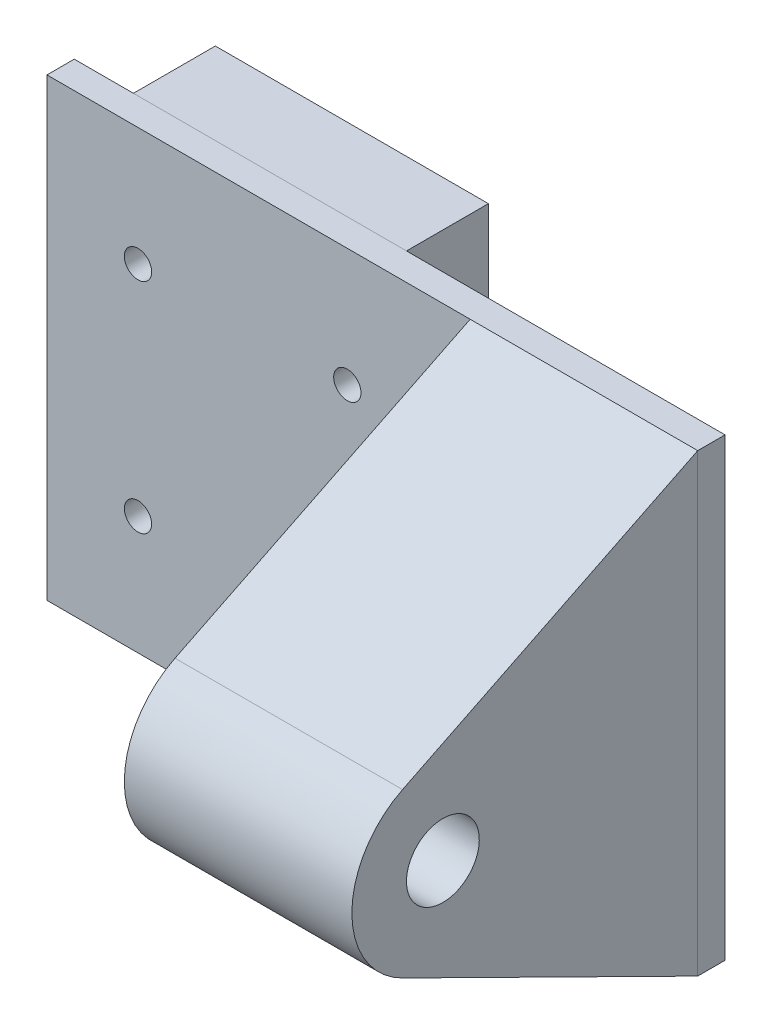
SolidWorks part; units mm, degrees
ref_plane "Plan de face" through (0, 0, 0) normal (0, 0, 1) x (1, 0, 0)
ref_plane "Plan de dessus" through (0, 0, 0) normal (0, 1, 0) x (1, 0, 0)
ref_plane "Plan de droite" through (0, 0, 0) normal (1, 0, 0) x (0, 0, -1)
sketch "Esquisse1" plane through (0, 0, 0) normal (0, 0, 1) x (1, 0, 0)
  line L1 (0, 0) -> (30, 0)
  line L2 (0, 0) -> (0, 50)
  line L3 (0, 50) -> (30, 50)
  line L4 (30, 0) -> (30, 50)
  dimension "D1" = 30
  dimension "D2" = 50
extrude "Boss.-Extru.1" add sketch "Esquisse1" along normal blind 9
sketch "Esquisse2" plane through (0, 0, 9) normal (0, 0, 1) x (1, 0, 0)
  line L0 (0, 0) -> (30, 0) construction
  line L1 (-6.5, 50) -> (65, 50)
  line L2 (-6.5, 50) -> (-6.5, 0)
  line L3 (-6.5, 0) -> (65, 0)
  line L4 (65, 50) -> (65, 0)
  line L5 (30, 50) -> (0, 50) construction
  line L6 (30, 50) -> (0, 50) construction
  line L7 (0, 50) -> (0, 0) construction
  point P7 (15, 50)
  dimension "D1" = 50
  dimension "D2" = 6.5
extrude "Boss.-Extru.2" add sketch "Esquisse2" along normal blind 3 separate body
sketch "Esquisse3" plane through (65, 0, 0) normal (1, 0, 0) x (0, 0, -1)
  line L0 (-12, 50) -> (-12, 0)
  line L1 (-12, 0) -> (-44.4322, 16.0359)
  line L3 (-44.4322, 33.9641) -> (-12, 50)
  line L4 (0, 0) -> (0, 50) construction
  circle A0 centre (-40, 25) radius 4
  arc A1 (-44.4322, 33.9641) -> (-44.4322, 16.0359) centre (-40, 25) ccw
  dimension "D1" = 8
  dimension "D2" = 20
  dimension "D3" = 40
  dimension "D4" = 25
extrude "Boss.-Extru.3" add sketch "Esquisse3" against normal blind 25 separate body
sketch "Esquisse4" plane through (0, 0, 12) normal (0, 0, 1) x (1, 0, 0)
  line L0 (15, 37) -> (15, 25) construction
  line L1 (15, 25) -> (26.5, 25) construction
  line L2 (-6.5, 50) -> (-6.5, 0) construction
  line L3 (0, 0) -> (30, 0) construction
  circle A0 centre (26.5, 37) radius 1.5
  circle A1 centre (26.5, 13) radius 1.5
  circle A2 centre (3.5, 13) radius 1.5
  circle A3 centre (3.5, 37) radius 1.5
  point P13 (-6.5, 25)
  point P16 (15, 0)
  dimension "D1" = 23
  dimension "D2" = 3
  dimension "D3" = 24
extrude "Enlèv. mat.-Extru.1" cut sketch "Esquisse4" against normal through all
